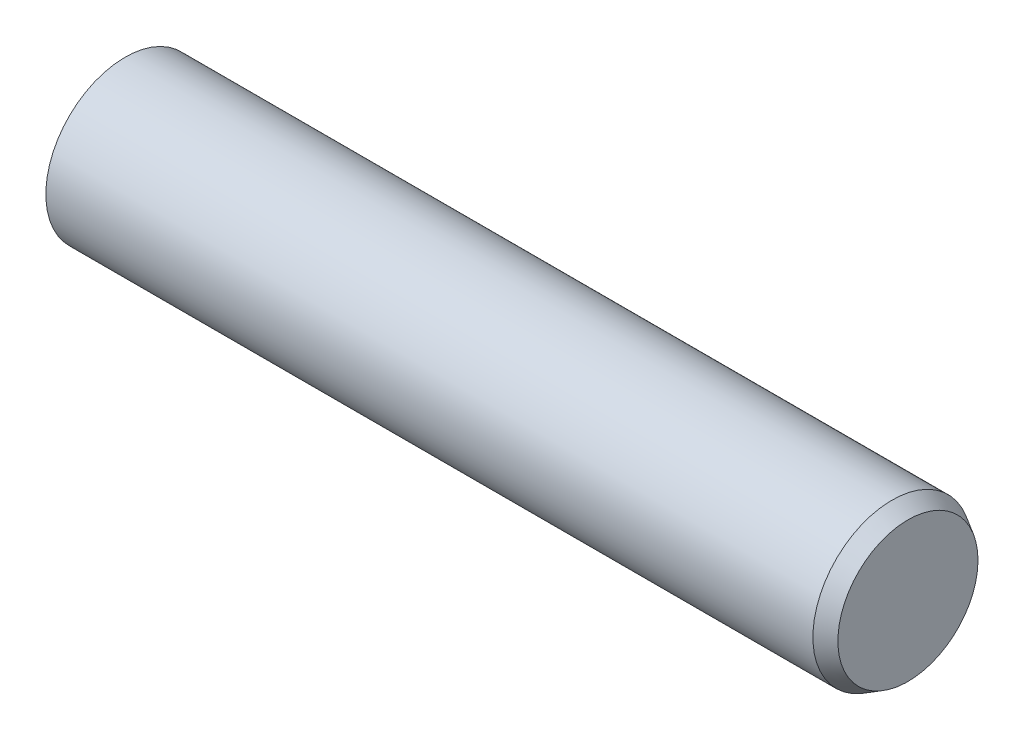
SolidWorks part; units mm, degrees
material "Cedar"
ref_plane "Front Plane" through (0, 0, 0) normal (0, 0, 1) x (1, 0, 0)
ref_plane "Top Plane" through (0, 0, 0) normal (0, 1, 0) x (1, 0, 0)
ref_plane "Right Plane" through (0, 0, 0) normal (1, 0, 0) x (0, 0, -1)
sketch "Sketch1" plane through (0, 0, 0) normal (1, 0, 0) x (0, 0, -1)
  circle A0 centre (0, 0) radius 10
  dimension "D1" = 20
extrude "Boss-Extrude1" add sketch "Sketch1" along normal mid plane 100
sketch "Sketch2" plane through (50, 0, 0) normal (1, 0, 0) x (0, 0, -1)
  circle A0 centre (0, 0) radius 10 construction
  point P0 (0, 10)
chamfer "Chamfer1" distance 2 angle 30 2 edges at (-50, 0, -10) (50, 0, -10)
